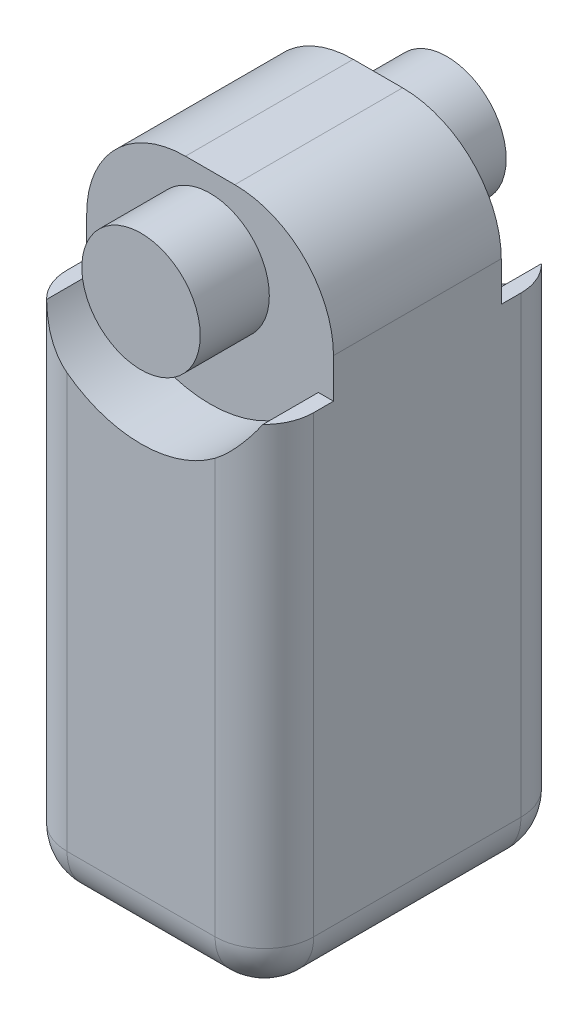
SolidWorks part; units mm, degrees
ref_plane "Alzado" through (0, 0, 0) normal (0, 0, 1) x (1, 0, 0)
ref_plane "Planta" through (0, 0, 0) normal (0, 1, 0) x (1, 0, 0)
ref_plane "Vista lateral" through (0, 0, 0) normal (1, 0, 0) x (0, 0, -1)
sketch "Croquis1" plane through (0, 0, 0) normal (0, 0, 1) x (1, 0, 0)
  line L1 (-2.269, 17.2602) -> (22.731, 17.2602)
  line L2 (-2.269, 17.2602) -> (-2.269, -47.7398)
  line L3 (-2.269, -47.7398) -> (22.731, -47.7398)
  line L4 (22.731, 17.2602) -> (22.731, -47.7398)
  dimension "D1" = 65
  dimension "D2" = 25
extrude "Saliente-Extruir1" add sketch "Croquis1" along normal mid plane 31
sketch "Croquis2" plane through (0, 0, 15.5) normal (0, 0, 1) x (1, 0, 0)
  line L0 (-2.269, 17.2602) -> (-2.269, -47.7398) construction
  line L1 (22.731, 17.2602) -> (-2.269, 17.2602) construction
  line L2 (-2.269, 9.2602) -> (-2.269, 26.0583)
  line L3 (-2.269, 26.0583) -> (22.731, 26.0583)
  line L4 (22.731, 26.0583) -> (22.731, 9.2602)
  line L5 (-0.7349, 3.2602) -> (-2.269, 3.2602)
  line L6 (-2.269, 3.2602) -> (-2.269, 9.2602)
  line L7 (21.1968, 3.2602) -> (22.731, 3.2602)
  line L8 (22.731, -47.7398) -> (22.731, 17.2602) construction
  line L9 (22.731, 9.2602) -> (22.731, 3.2602)
  arc A0 (-0.7349, 3.2602) -> (21.1968, 3.2602) centre (10.231, 9.2602) ccw
  circle A1 centre (10.231, 9.2602) radius 6
  dimension "D1" = 25
  dimension "D3" = 12
  dimension "D2" = 8
extrude "Cortar-Extruir1" cut sketch "Croquis2" against normal blind 7
mirror "Simetría1" about plane through (0, 0, 0) normal (0, 0, 1) of "Cortar-Extruir1"
fillet "Redondeo1" radius 10 2 edges at (-2.269, 17.2602, 0) (22.731, 17.2602, 0)
fillet "Redondeo2" radius 5 4 edges at (22.731, -22.2398, -15.5) (22.731, -22.2398, 15.5) (-2.269, -22.2398, 15.5) (-2.269, -22.2398, -15.5)
sketch "Croquis3" plane through (0, -47.7398, 0) normal (0, -1, 0) x (1, 0, 0)
  line L0 (2.731, 15.5) -> (17.731, 15.5) construction
  line L1 (-2.269, 10.5) -> (-2.269, -10.5) construction
  circle A0 centre (10.231, 0) radius 5
  dimension "D1" = 10
  dimension "D2" = 15.5
  dimension "D3" = 12.5
extrude "Cortar-Extruir2" cut sketch "Croquis3" against normal blind 5.5
fillet "Redondeo3" radius 5 8 edges at (-0.8046, -47.7398, 14.0355) (21.2665, -47.7398, 14.0355) (21.2665, -47.7398, -14.0355) (-0.8046, -47.7398, -14.0355) (10.231, -47.7398, -15.5) (22.731, -47.7398, 0) (10.231, -47.7398, 15.5) (-2.269, -47.7398, 0)
